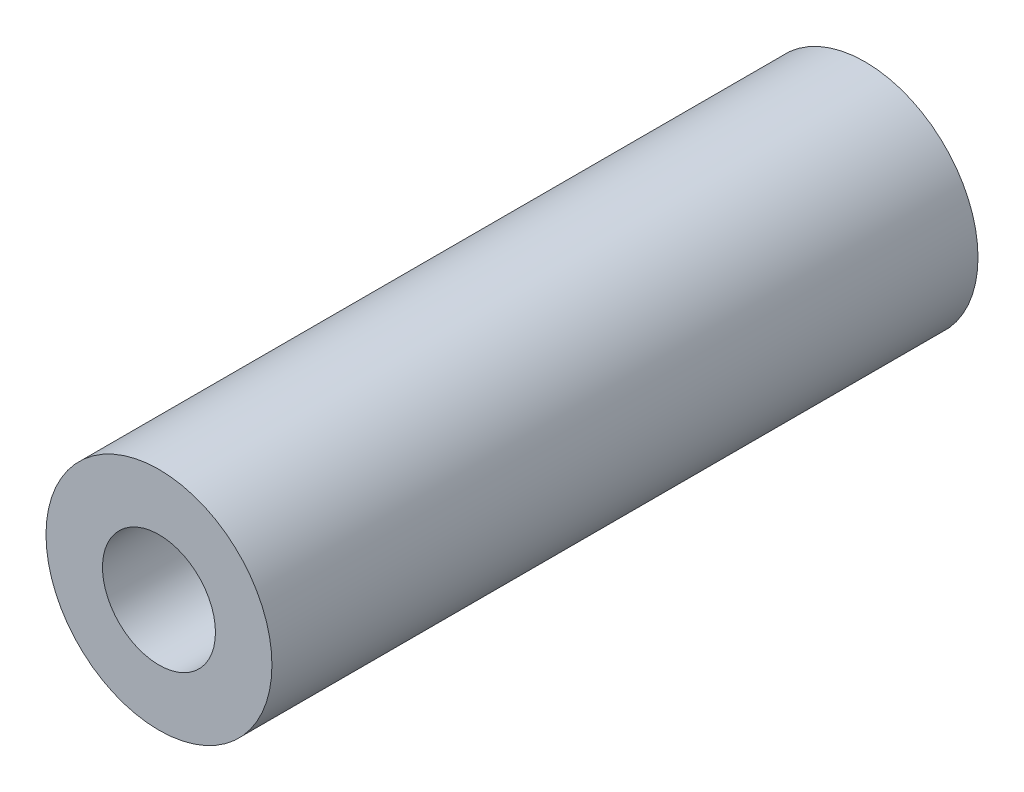
SolidWorks part; units mm, degrees
ref_plane "Front Plane" through (0, 0, 0) normal (0, 0, 1) x (1, 0, 0)
ref_plane "Top Plane" through (0, 0, 0) normal (0, 1, 0) x (1, 0, 0)
ref_plane "Right Plane" through (0, 0, 0) normal (1, 0, 0) x (0, 0, -1)
sketch "Sketch1" plane through (0, 0, 0) normal (0, 0, 1) x (1, 0, 0)
  circle A0 centre (0, 0) radius 2.54
  circle A1 centre (0, 0) radius 5.08
  dimension "D1" = 5.08
  dimension "D2" = 10.16
extrude "Boss-Extrude1" add sketch "Sketch1" along normal blind 31.75
